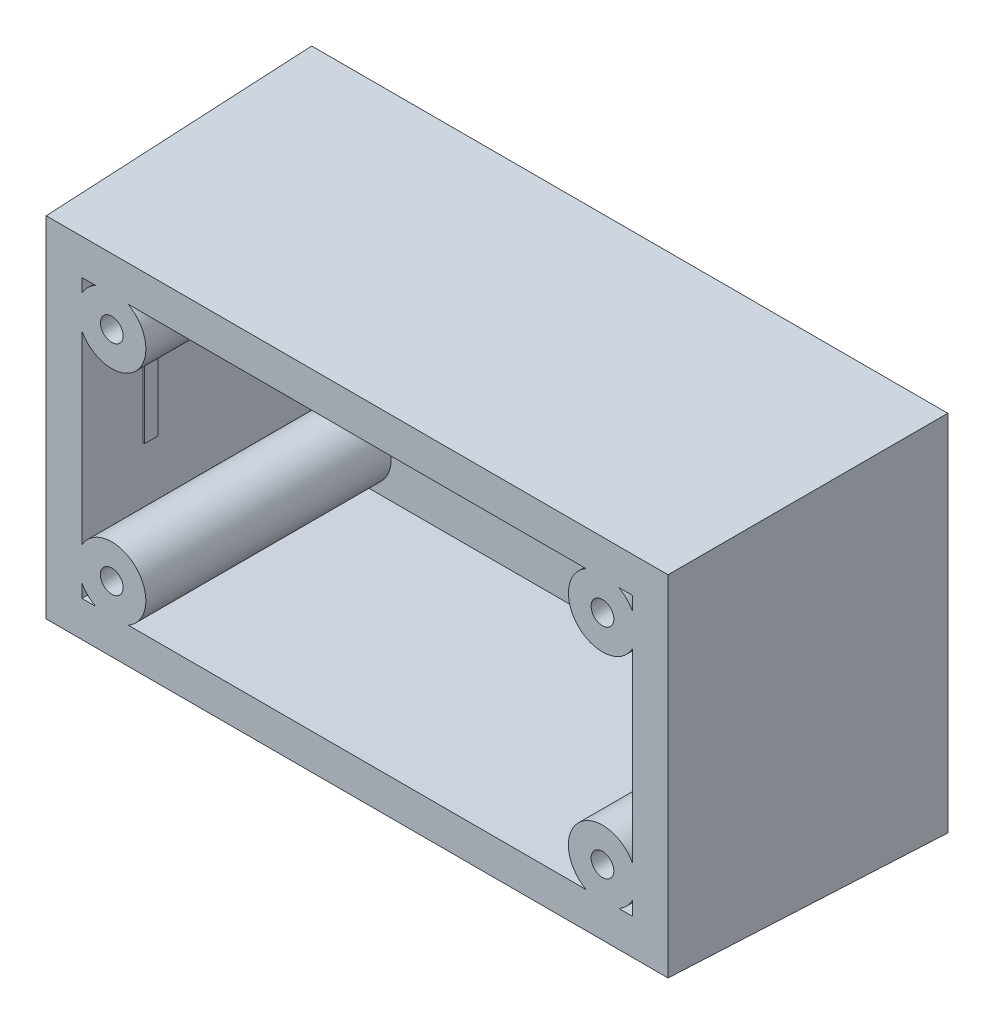
SolidWorks part; units mm, degrees
ref_plane "Front Plane" through (0, 0, 0) normal (0, 0, 1) x (1, 0, 0)
ref_plane "Top Plane" through (0, 0, 0) normal (0, 1, 0) x (1, 0, 0)
ref_plane "Right Plane" through (0, 0, 0) normal (1, 0, 0) x (0, 0, -1)
other "Configuration Table"
sketch "Sketch2" plane through (0, 0, 0) normal (0, 0, 1) x (1, 0, 0)
  line L1 (-35, -20) -> (35, -20)
  line L2 (-35, -20) -> (-35, 20)
  line L3 (-35, 20) -> (35, 20)
  line L4 (35, -20) -> (35, 20)
extrude "Drafted_outer_shell" add sketch "Sketch2" along normal blind 30 draft 1.5
sketch "Sketch3" plane through (0, 0, 0) normal (0, 0, 1) x (1, 0, 0)
  line L1 (-31, -16) -> (31, -16)
  line L2 (-31, -16) -> (-31, 16)
  line L3 (-31, 16) -> (31, 16)
  line L4 (31, -16) -> (31, 16)
extrude "Drafted_cavity" cut sketch "Sketch3" along normal blind 27 draft 1.5 from offset 3
sketch "Sketch4" plane through (0, 0, 0) normal (0, 0, 1) x (1, 0, 0)
  circle A0 centre (-27, -12) radius 3.75
extrude "Screw_boss" add sketch "Sketch4" along normal blind 27 from offset 3
sketch "Sketch5" plane through (0, 0, 0) normal (0, 0, 1) x (1, 0, 0)
  circle A0 centre (-27, -12) radius 1.25
extrude "Screw_boss_bore" cut sketch "Sketch5" along normal blind 27 from offset 3
sketch "Sketch6" plane through (0, 0, 0) normal (0, 0, 1) x (1, 0, 0)
  circle A0 centre (-27, 12) radius 3.75
extrude "Boss-Extrude3" add sketch "Sketch6" along normal blind 27 from offset 3
sketch "Sketch7" plane through (0, 0, 0) normal (0, 0, 1) x (1, 0, 0)
  circle A0 centre (-27, 12) radius 1.25
extrude "Cut-Extrude3" cut sketch "Sketch7" along normal blind 27 from offset 3
sketch "Sketch8" plane through (0, 0, 0) normal (0, 0, 1) x (1, 0, 0)
  circle A0 centre (27, -12) radius 3.75
extrude "Boss-Extrude4" add sketch "Sketch8" along normal blind 27 from offset 3
sketch "Sketch9" plane through (0, 0, 0) normal (0, 0, 1) x (1, 0, 0)
  circle A0 centre (27, -12) radius 1.25
extrude "Cut-Extrude4" cut sketch "Sketch9" along normal blind 27 from offset 3
sketch "Sketch10" plane through (0, 0, 0) normal (0, 0, 1) x (1, 0, 0)
  circle A0 centre (27, 12) radius 3.75
extrude "Boss-Extrude5" add sketch "Sketch10" along normal blind 27 from offset 3
sketch "Sketch11" plane through (0, 0, 0) normal (0, 0, 1) x (1, 0, 0)
  circle A0 centre (27, 12) radius 1.25
extrude "Cut-Extrude5" cut sketch "Sketch11" along normal blind 27 from offset 3
sketch "Sketch12" plane through (0, 0, 0) normal (0, 0, 1) x (1, 0, 0)
  line L0 (-30.293, 10.2059) -> (-30.293, -10.2059) construction
  line L1 (-32.4, -4) -> (-30.293, -4)
  line L2 (-32.4, -4) -> (-32.4, 4)
  line L3 (-32.4, 4) -> (-30.293, 4)
  line L4 (-30.293, -4) -> (-30.293, 4)
extrude "Snap_catch_ledge" add sketch "Sketch12" along normal blind 1.5 from offset 21.6
sketch "Sketch13" plane through (0, 0, 0) normal (0, 0, 1) x (1, 0, 0)
  line L0 (30.293, -10.2059) -> (30.293, 10.2059) construction
  line L1 (30.293, -4) -> (32.4, -4)
  line L2 (30.293, -4) -> (30.293, 4)
  line L3 (30.293, 4) -> (32.4, 4)
  line L4 (32.4, -4) -> (32.4, 4)
extrude "Boss-Extrude7" add sketch "Sketch13" along normal blind 1.5 from offset 21.6
